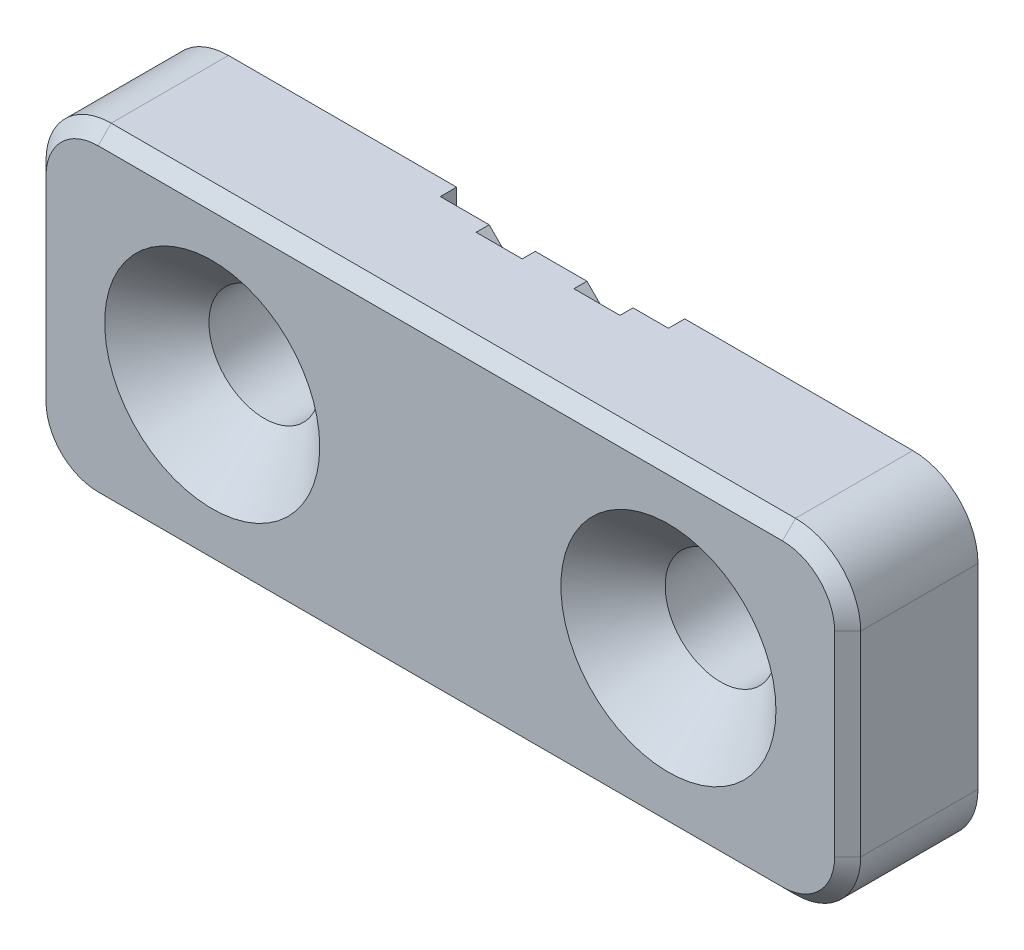
SolidWorks part; units mm, degrees
ref_plane "前视基准面" through (0, 0, 0) normal (0, 0, 1) x (1, 0, 0)
ref_plane "上视基准面" through (0, 0, 0) normal (0, 1, 0) x (1, 0, 0)
ref_plane "右视基准面" through (0, 0, 0) normal (1, 0, 0) x (0, 0, -1)
sketch "草图1" plane through (0, 0, 0) normal (0, 0, 1) x (1, 0, 0)
  line L1 (-12.5, -5) -> (12.5, -5)
  line L2 (-12.5, -5) -> (-12.5, 5)
  line L3 (-12.5, 5) -> (12.5, 5)
  line L4 (12.5, -5) -> (12.5, 5)
  line L5 (-12.5, -5) -> (12.5, 5) construction
  line L6 (-12.5, 5) -> (12.5, -5) construction
  point P0 (0, 0)
  dimension "D1" = 25
  dimension "D2" = 10
extrude "凸台-拉伸1" add sketch "草图1" along normal blind 4
sketch "草图2" plane through (0, 5, 0) normal (0, 1, 0) x (1, 0, 0)
  line L0 (12.5, 0) -> (-12.5, 0) construction
  line L1 (-3.5, -0.5) -> (3.5, -0.5)
  line L2 (-3.5, -0.5) -> (-3.5, 0.5)
  line L3 (-3.5, 0.5) -> (3.5, 0.5)
  line L4 (3.5, -0.5) -> (3.5, 0.5)
  line L5 (-3.5, -0.5) -> (3.5, 0.5) construction
  line L6 (-3.5, 0.5) -> (3.5, -0.5) construction
  line L7 (12.5, -4) -> (12.5, 0) construction
  point P0 (0, 0)
  point P10 (0, 0)
  dimension "D1" = 0.5
  dimension "D2" = 9
extrude "切除-拉伸1" cut sketch "草图2" against normal through all
sketch "草图3" plane through (0, 0, 4) normal (0, 0, 1) x (1, 0, 0)
  circle A0 centre (7, 0) radius 1.5
  point P0 (7, 0)
  dimension "D2" = 3
  dimension "D1" = 7
hole_wizard "M3 十字槽沉头木螺钉的锥形沉头孔1" positions "草图3" profile "草图4" countersink size "M3" standard "GB" end condition through all
sketch "草图4" plane through (7, 0, 4) normal (1, 0, 0) x (0, -1, 0)
  line L0 (0, 0) -> (0, 4)
  line L1 (0, 4) -> (1.7, 4)
  line L2 (1.7, 4) -> (1.7, 1.6)
  line L3 (1.7, 1.6) -> (3.3, 0)
  line L5 (3.3, 0) -> (0, 0)
  line L6 (-1.7, 1.6) -> (-3.3, 0) construction
  line L11 (0, -6.35) -> (0, 107.95) construction
  dimension "通孔孔直径" = 3.4
  dimension "通孔孔深度" = 4
  dimension "近端锥形沉头孔直径" = 6.6
  dimension "近端锥形沉头孔角度" = 90
mirror "镜向1" about plane through (0, 0, 0) normal (1, 0, 0) of "M3 十字槽沉头木螺钉的锥形沉头孔1"
fillet "圆角1" radius 2 4 edges at (-12.5, 5, 2) (-12.5, -5, 2) (12.5, -5, 2) (12.5, 5, 2)
chamfer "倒角1" distance 0.4 angle 45 8 edges at (-11.9142, 4.4142, 4) (-12.5, 0, 4) (0, 5, 4) (-11.9142, -4.4142, 4) (11.9142, 4.4142, 4) (0, -5, 4) (12.5, 0, 4) (11.9142, -4.4142, 4)
sketch "草图5" plane through (0, 0, 0.5) normal (0, 0, -1) x (-1, 0, 0)
  line L50 (-3.5, -3.5) -> (3.5, 3.5)
  line L51 (-3.5, -5) -> (-3.5, 5) construction
  line L54 (3.5, -5) -> (3.5, 5) construction
  line L55 (-3.5, -2.0858) -> (3.5, 4.9142)
  line L57 (3.5, 4.9142) -> (3.5, 3.5)
  line L59 (-3.5, -2.0858) -> (-3.5, -3.5)
  line L63 (-3.5, -0.5) -> (3.5, 6.5)
  line L64 (-3.5, 0.9142) -> (3.5, 7.9142)
  line L68 (3.5, 7.9142) -> (3.5, 6.5)
  line L69 (-3.5, 0.9142) -> (-3.5, -0.5)
  line L72 (-3.5, 2.5) -> (3.5, 9.5)
  line L73 (-3.5, 3.9142) -> (3.5, 10.9142)
  line L76 (3.5, 10.9142) -> (3.5, 9.5)
  line L77 (-3.5, 3.9142) -> (-3.5, 2.5)
  line L80 (-3.5, -3.5) -> (3.5, 3.5)
  line L81 (-3.5, -2.0858) -> (3.5, 4.9142)
  line L84 (3.5, 4.9142) -> (3.5, 3.5)
  line L85 (-3.5, -2.0858) -> (-3.5, -3.5)
  line L88 (-3.5, -0.5) -> (3.5, 6.5)
  line L89 (-3.5, 0.9142) -> (3.5, 7.9142)
  line L90 (3.5, 7.9142) -> (3.5, 6.5)
  line L91 (-3.5, 0.9142) -> (-3.5, -0.5)
  line L92 (-3.5, -6.5) -> (3.5, 0.5)
  line L93 (-3.5, -5.0858) -> (3.5, 1.9142)
  line L94 (3.5, 1.9142) -> (3.5, 0.5)
  line L95 (-3.5, -5.0858) -> (-3.5, -6.5)
  line L96 (-3.5, -3.5) -> (3.5, 3.5)
  line L97 (-3.5, -2.0858) -> (3.5, 4.9142)
  line L98 (3.5, 4.9142) -> (3.5, 3.5)
  line L99 (-3.5, -2.0858) -> (-3.5, -3.5)
  line L100 (-3.5, -9.5) -> (3.5, -2.5)
  line L101 (-3.5, -8.0858) -> (3.5, -1.0858)
  line L102 (3.5, -1.0858) -> (3.5, -2.5)
  line L103 (-3.5, -8.0858) -> (-3.5, -9.5)
  line L104 (-3.5, -6.5) -> (3.5, 0.5)
  line L105 (-3.5, -5.0858) -> (3.5, 1.9142)
  line L106 (3.5, 1.9142) -> (3.5, 0.5)
  line L107 (-3.5, -5.0858) -> (-3.5, -6.5)
  line L108 (-3.5, -6.5) -> (3.5, 0.5)
  line L109 (-3.5, -5.0858) -> (3.5, 1.9142)
  line L110 (3.5, 1.9142) -> (3.5, 0.5)
  line L111 (-3.5, -5.0858) -> (-3.5, -6.5)
  line L112 (-3.5, -9.5) -> (3.5, -2.5)
  line L113 (-3.5, -8.0858) -> (3.5, -1.0858)
  line L114 (3.5, -1.0858) -> (3.5, -2.5)
  line L115 (-3.5, -8.0858) -> (-3.5, -9.5)
  line L116 (-3.5, -12.5) -> (3.5, -5.5)
  line L117 (-3.5, -11.0858) -> (3.5, -4.0858)
  line L118 (3.5, -4.0858) -> (3.5, -5.5)
  line L119 (-3.5, -11.0858) -> (-3.5, -12.5)
  dimension "D1" = 45
  dimension "D2" = 1
  dimension "D3" = 3
  dimension "D4" = 4
extrude "切除-拉伸2" cut sketch "草图5" against normal blind 0.4
